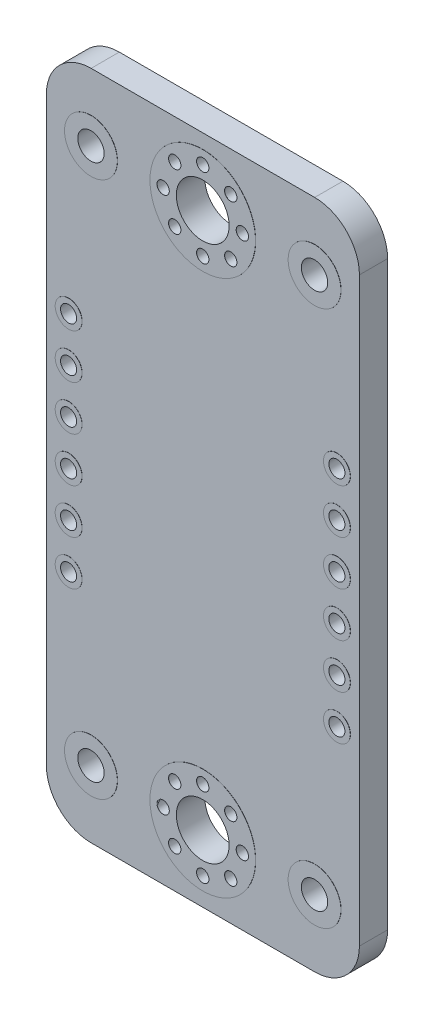
SolidWorks part; units mm, degrees
ref_plane "Front Plane" through (0, 0, 0) normal (0, 0, 1) x (1, 0, 0)
ref_plane "Top Plane" through (0, 0, 0) normal (0, 1, 0) x (1, 0, 0)
ref_plane "Right Plane" through (0, 0, 0) normal (1, 0, 0) x (0, 0, -1)
sketch "Model" plane through (0, 0, 0) normal (0, 0, 1) x (1, 0, 0)
  line L0 (2.54, 0) -> (15.24, 0)
  line L1 (0, -35.56) -> (0, -2.54)
  line L2 (15.24, -38.1) -> (2.54, -38.1)
  line L3 (17.78, -2.54) -> (17.78, -35.56)
  arc A0 (17.78, -2.54) -> (15.24, 0) centre (15.24, -2.54) ccw
  arc A1 (15.24, -38.1) -> (17.78, -35.56) centre (15.24, -35.56) ccw
  arc A2 (0, -35.56) -> (2.54, -38.1) centre (2.54, -35.56) ccw
  arc A3 (2.54, 0) -> (0, -2.54) centre (2.54, -2.54) ccw
  circle A4 centre (16.51, -15.24) radius 0.4572
  circle A5 centre (16.51, -15.24) radius 0.762 construction
  circle A6 centre (16.51, -17.78) radius 0.4572
  circle A7 centre (16.51, -17.78) radius 0.762 construction
  circle A8 centre (16.51, -20.32) radius 0.4572
  circle A9 centre (16.51, -20.32) radius 0.762 construction
  circle A10 centre (16.51, -22.86) radius 0.4572
  circle A11 centre (16.51, -22.86) radius 0.762 construction
  circle A12 centre (16.51, -25.4) radius 0.4572
  circle A13 centre (16.51, -25.4) radius 0.762 construction
  circle A14 centre (1.27, -25.4) radius 0.4572
  circle A15 centre (1.27, -25.4) radius 0.762 construction
  circle A16 centre (1.27, -22.86) radius 0.4572
  circle A17 centre (1.27, -22.86) radius 0.762 construction
  circle A18 centre (1.27, -20.32) radius 0.4572
  circle A19 centre (1.27, -20.32) radius 0.762 construction
  circle A20 centre (1.27, -17.78) radius 0.4572
  circle A21 centre (1.27, -17.78) radius 0.762 construction
  circle A22 centre (1.27, -15.24) radius 0.4572
  circle A23 centre (1.27, -15.24) radius 0.762 construction
  circle A24 centre (1.27, -12.7) radius 0.4572
  circle A25 centre (1.27, -12.7) radius 0.762 construction
  circle A26 centre (8.89, -3.81) radius 1.5
  circle A27 centre (8.89, -3.81) radius 3 construction
  circle A28 centre (11.14, -3.81) radius 0.35
  circle A29 centre (11.1399, -3.81) radius 0.75 construction
  circle A30 centre (6.64, -3.81) radius 0.35
  circle A31 centre (6.6401, -3.81) radius 0.75 construction
  circle A32 centre (8.89, -1.5601) radius 0.35
  circle A33 centre (8.89, -1.5601) radius 0.75 construction
  circle A34 centre (8.89, -6.0599) radius 0.35
  circle A35 centre (8.89, -6.0599) radius 0.75 construction
  circle A36 centre (10.4811, -5.4011) radius 0.35
  circle A37 centre (10.4811, -5.4011) radius 0.75 construction
  circle A38 centre (10.4811, -2.2189) radius 0.35
  circle A39 centre (10.4811, -2.2189) radius 0.75 construction
  circle A40 centre (7.2989, -2.2189) radius 0.35
  circle A41 centre (7.2989, -2.2189) radius 0.75 construction
  circle A42 centre (7.2989, -5.4011) radius 0.35
  circle A43 centre (7.2989, -5.4011) radius 0.75 construction
  circle A44 centre (8.89, -34.29) radius 1.5
  circle A45 centre (8.89, -34.29) radius 3 construction
  circle A46 centre (11.14, -34.29) radius 0.35
  circle A47 centre (11.1399, -34.29) radius 0.75 construction
  circle A48 centre (6.64, -34.29) radius 0.35
  circle A49 centre (6.6401, -34.29) radius 0.75 construction
  circle A50 centre (8.89, -32.0401) radius 0.35
  circle A51 centre (8.89, -32.0401) radius 0.75 construction
  circle A52 centre (8.89, -36.5399) radius 0.35
  circle A53 centre (8.89, -36.5399) radius 0.75 construction
  circle A54 centre (10.4811, -35.8811) radius 0.35
  circle A55 centre (10.4811, -35.8811) radius 0.75 construction
  circle A56 centre (10.4811, -32.6989) radius 0.35
  circle A57 centre (10.4811, -32.6989) radius 0.75 construction
  circle A58 centre (7.2989, -32.6989) radius 0.35
  circle A59 centre (7.2989, -32.6989) radius 0.75 construction
  circle A60 centre (7.2989, -35.8811) radius 0.35
  circle A61 centre (7.2989, -35.8811) radius 0.75 construction
  circle A62 centre (2.54, -3.81) radius 0.75
  circle A63 centre (2.54, -3.81) radius 1.5 construction
  circle A64 centre (15.24, -3.81) radius 0.75
  circle A65 centre (15.24, -3.81) radius 1.5 construction
  circle A66 centre (15.24, -34.29) radius 0.75
  circle A67 centre (15.24, -34.29) radius 1.5 construction
  circle A68 centre (2.54, -34.29) radius 0.75
  circle A69 centre (2.54, -34.29) radius 1.5 construction
  circle A70 centre (16.51, -12.7) radius 0.4572
  circle A71 centre (11.938, -12.446) radius 0.31 construction
  circle A72 centre (11.938, -12.446) radius 0.155 construction
  circle A73 centre (5.842, -12.446) radius 0.31 construction
  circle A74 centre (5.842, -12.446) radius 0.155 construction
  circle A75 centre (5.842, -18.796) radius 0.31 construction
  circle A76 centre (5.842, -18.796) radius 0.155 construction
  circle A77 centre (11.938, -18.796) radius 0.31 construction
  circle A78 centre (11.938, -18.796) radius 0.155 construction
  circle A79 centre (5.842, -25.146) radius 0.31 construction
  circle A80 centre (5.842, -25.146) radius 0.155 construction
  circle A81 centre (11.938, -25.146) radius 0.31 construction
  circle A82 centre (11.938, -25.146) radius 0.155 construction
  circle A83 centre (1.27, -30.48) radius 0.31 construction
  circle A84 centre (1.27, -30.48) radius 0.155 construction
  circle A85 centre (16.51, -30.48) radius 0.31 construction
  circle A86 centre (16.51, -30.48) radius 0.155 construction
  circle A87 centre (12.7, -36.83) radius 0.31 construction
  circle A88 centre (12.7, -36.83) radius 0.155 construction
  circle A89 centre (5.08, -36.83) radius 0.31 construction
  circle A90 centre (5.08, -36.83) radius 0.155 construction
  circle A91 centre (2.54, -36.83) radius 0.31 construction
  circle A92 centre (2.54, -36.83) radius 0.155 construction
  circle A93 centre (15.24, -36.83) radius 0.31 construction
  circle A94 centre (15.24, -36.83) radius 0.155 construction
  circle A95 centre (16.51, -27.94) radius 0.31 construction
  circle A96 centre (16.51, -27.94) radius 0.155 construction
  circle A97 centre (1.27, -27.94) radius 0.31 construction
  circle A98 centre (1.27, -27.94) radius 0.155 construction
  circle A99 centre (1.27, -10.16) radius 0.31 construction
  circle A100 centre (1.27, -10.16) radius 0.155 construction
  circle A101 centre (1.27, -7.62) radius 0.31 construction
  circle A102 centre (1.27, -7.62) radius 0.155 construction
  circle A103 centre (16.51, -7.62) radius 0.31 construction
  circle A104 centre (16.51, -7.62) radius 0.155 construction
  circle A105 centre (16.51, -10.16) radius 0.31 construction
  circle A106 centre (16.51, -10.16) radius 0.155 construction
  circle A107 centre (12.7, -1.27) radius 0.31 construction
  circle A108 centre (12.7, -1.27) radius 0.155 construction
  circle A109 centre (5.08, -1.27) radius 0.31 construction
  circle A110 centre (5.08, -1.27) radius 0.155 construction
  circle A111 centre (12.7, -6.35) radius 0.31 construction
  circle A112 centre (12.7, -6.35) radius 0.155 construction
  circle A113 centre (15.24, -6.35) radius 0.31 construction
  circle A114 centre (15.24, -6.35) radius 0.155 construction
  circle A115 centre (15.24, -1.27) radius 0.31 construction
  circle A116 centre (15.24, -1.27) radius 0.155 construction
  circle A117 centre (2.54, -1.27) radius 0.31 construction
  circle A118 centre (2.54, -1.27) radius 0.155 construction
  circle A119 centre (14.4694, -13.462) radius 0.31 construction
  circle A120 centre (14.4694, -13.462) radius 0.155 construction
  circle A121 centre (12.7, -15.494) radius 0.31 construction
  circle A122 centre (12.7, -15.494) radius 0.155 construction
  circle A123 centre (12.7, -21.844) radius 0.31 construction
  circle A124 centre (12.7, -21.844) radius 0.155 construction
  circle A125 centre (12.7, -28.194) radius 0.31 construction
  circle A126 centre (12.7, -28.194) radius 0.155 construction
  circle A127 centre (5.08, -28.194) radius 0.31 construction
  circle A128 centre (5.08, -28.194) radius 0.155 construction
  circle A129 centre (5.08, -21.844) radius 0.31 construction
  circle A130 centre (5.08, -21.844) radius 0.155 construction
  circle A131 centre (5.08, -15.494) radius 0.31 construction
  circle A132 centre (5.08, -15.494) radius 0.155 construction
  circle A133 centre (5.08, -9.144) radius 0.31 construction
  circle A134 centre (5.08, -9.144) radius 0.155 construction
  circle A135 centre (12.7, -9.144) radius 0.31 construction
  circle A136 centre (12.7, -9.144) radius 0.155 construction
extrude "Boss-Extrude1" add sketch "Model" along normal blind 1.6
ref_plane "Plane1" through (8.89, 0, 0) normal (1, 0, 0) x (0, 0, -1)
ref_plane "Plane2" through (0, -19.05, 0) normal (0, 1, 0) x (1, 0, 0)
sketch "Sketch1" plane through (0, 0, 1.6) normal (0, 0, 1) x (1, 0, 0)
  line L0 (17.78, -19.05) -> (0, -19.05) construction
  line L1 (17.78, -2.54) -> (17.78, -35.56) construction
  line L2 (0, -35.56) -> (0, -2.54) construction
  line L3 (8.89, -3.81) -> (8.89, -34.29) construction
  circle A0 centre (8.89, -3.81) radius 3
  circle A2 centre (2.54, -3.81) radius 1.5
  circle A6 centre (1.27, -20.32) radius 0.762
  circle A7 centre (1.27, -22.86) radius 0.762
  circle A8 centre (1.27, -25.4) radius 0.762
  circle A17 centre (2.54, -3.81) radius 0.75
  circle A18 centre (2.54, -3.81) radius 0.75 construction
  circle A19 centre (2.54, -3.81) radius 1.5 construction
  circle A20 centre (8.89, -3.81) radius 3 construction
  circle A21 centre (8.89, -3.81) radius 1.5
  circle A22 centre (8.89, -3.81) radius 1.5 construction
  circle A26 centre (8.89, -1.5601) radius 0.35
  circle A28 centre (8.89, -1.5601) radius 0.35 construction
  circle A29 centre (10.4809, -2.2192) radius 0.35
  circle A30 centre (11.1398, -3.8103) radius 0.35
  circle A31 centre (10.4807, -5.4012) radius 0.35
  circle A32 centre (8.8896, -6.0601) radius 0.35
  circle A33 centre (7.2987, -5.4009) radius 0.35
  circle A34 centre (6.6398, -3.8099) radius 0.35
  circle A35 centre (7.2989, -2.2189) radius 0.35
  circle A36 centre (15.24, -3.81) radius 1.5
  circle A37 centre (15.24, -3.81) radius 0.75
  circle A38 centre (15.24, -3.81) radius 0.75 construction
  circle A39 centre (15.24, -3.81) radius 1.5 construction
  circle A40 centre (15.24, -34.29) radius 0.75
  circle A41 centre (15.24, -34.29) radius 1.5
  circle A42 centre (7.2989, -35.8811) radius 0.35
  circle A43 centre (6.6398, -34.2901) radius 0.35
  circle A44 centre (7.2987, -32.6991) radius 0.35
  circle A45 centre (8.8896, -32.0399) radius 0.35
  circle A46 centre (10.4807, -32.6988) radius 0.35
  circle A47 centre (11.1398, -34.2897) radius 0.35
  circle A48 centre (10.4809, -35.8808) radius 0.35
  circle A49 centre (8.89, -36.5399) radius 0.35
  circle A50 centre (8.89, -34.29) radius 1.5
  circle A51 centre (2.54, -34.29) radius 0.75
  circle A52 centre (2.54, -34.29) radius 1.5
  circle A53 centre (8.89, -34.29) radius 3
  circle A54 centre (1.27, -25.4) radius 0.762 construction
  circle A57 centre (1.27, -22.86) radius 0.762 construction
  circle A58 centre (1.27, -20.32) radius 0.762 construction
  circle A59 centre (1.27, -20.32) radius 0.4572
  circle A60 centre (1.27, -22.86) radius 0.4572
  circle A61 centre (1.27, -25.4) radius 0.4572
  circle A62 centre (1.27, -20.32) radius 0.4572 construction
  circle A63 centre (1.27, -12.7) radius 0.4572
  circle A64 centre (1.27, -15.24) radius 0.4572
  circle A65 centre (1.27, -17.78) radius 0.4572
  circle A66 centre (1.27, -12.7) radius 0.762
  circle A67 centre (1.27, -15.24) radius 0.762
  circle A68 centre (1.27, -17.78) radius 0.762
  circle A69 centre (16.51, -17.78) radius 0.762
  circle A70 centre (16.51, -15.24) radius 0.762
  circle A71 centre (16.51, -12.7) radius 0.762
  circle A72 centre (16.51, -17.78) radius 0.4572
  circle A73 centre (16.51, -15.24) radius 0.4572
  circle A74 centre (16.51, -12.7) radius 0.4572
  circle A75 centre (16.51, -25.4) radius 0.4572
  circle A76 centre (16.51, -22.86) radius 0.4572
  circle A77 centre (16.51, -20.32) radius 0.4572
  circle A78 centre (16.51, -25.4) radius 0.762
  circle A79 centre (16.51, -22.86) radius 0.762
  circle A80 centre (16.51, -20.32) radius 0.762
  point P69 (8.8898, -3.8101)
  point P100 (8.8898, -34.2899)
  dimension "D1" = 8
extrude "Boss-Extrude2" add sketch "Sketch1" along normal blind 0.01
ref_plane "Plane3" through (0, 0, 0.8) normal (0, 0, 1) x (1, 0, 0)
mirror "Mirror1" about plane through (0, 0, 0.8) normal (0, 0, 1) of "Boss-Extrude2"
sketch "Sketch2" plane through (0, 0, 0) normal (0, 0, -1) x (-1, 0, 0)
  line L0 (-4.14, -8.05) -> (-2.89, -8.05)
  line L1 (-14.89, -8.05) -> (-13.64, -8.05)
  line L2 (-14.89, -8.05) -> (-14.89, -10.05)
  line L3 (-14.89, -10.05) -> (-13.64, -10.05)
  line L4 (-13.64, -8.05) -> (-13.64, -10.05)
  line L5 (-4.14, -8.05) -> (-4.14, -10.05)
  line L6 (-4.14, -10.05) -> (-2.89, -10.05)
  line L7 (-2.89, -8.05) -> (-2.89, -10.05)
  line L8 (-4.14, -14.7167) -> (-2.89, -14.7167)
  line L9 (-4.14, -14.7167) -> (-4.14, -16.7167)
  line L10 (-4.14, -16.7167) -> (-2.89, -16.7167)
  line L11 (-2.89, -14.7167) -> (-2.89, -16.7167)
  line L12 (-4.14, -21.3833) -> (-2.89, -21.3833)
  line L13 (-4.14, -21.3833) -> (-4.14, -23.3833)
  line L14 (-4.14, -23.3833) -> (-2.89, -23.3833)
  line L15 (-2.89, -21.3833) -> (-2.89, -23.3833)
  line L16 (-4.14, -28.05) -> (-2.89, -28.05)
  line L17 (-4.14, -28.05) -> (-4.14, -30.05)
  line L18 (-4.14, -30.05) -> (-2.89, -30.05)
  line L19 (-2.89, -28.05) -> (-2.89, -30.05)
  line L20 (-14.89, -14.7167) -> (-13.64, -14.7167)
  line L21 (-14.89, -14.7167) -> (-14.89, -16.7167)
  line L22 (-14.89, -16.7167) -> (-13.64, -16.7167)
  line L23 (-13.64, -14.7167) -> (-13.64, -16.7167)
  line L24 (-14.89, -21.3833) -> (-13.64, -21.3833)
  line L25 (-14.89, -21.3833) -> (-14.89, -23.3833)
  line L26 (-14.89, -23.3833) -> (-13.64, -23.3833)
  line L27 (-13.64, -21.3833) -> (-13.64, -23.3833)
  line L28 (-14.89, -28.05) -> (-13.64, -28.05)
  line L29 (-14.89, -28.05) -> (-14.89, -30.05)
  line L30 (-14.89, -30.05) -> (-13.64, -30.05)
  line L31 (-13.64, -28.05) -> (-13.64, -30.05)
  line L32 (0.88, -19.05) -> (-0.88, -19.05) construction
  line L33 (-8.89, 0.88) -> (-8.89, -0.88) construction
  point P5 (-12.7477, -27.0829)
  point P6 (-12.977, -7.4394)
  dimension "D1" = 2
  dimension "D2" = 1.25
  dimension "D5" = 11
  dimension "D6" = 22
  dimension "D7" = 12
  dimension "D8" = 6
  dimension "D3" = 2
  dimension "D4" = 4
extrude "Boss-Extrude3" add sketch "Sketch2" along normal blind 0.3
sketch "Sketch3" plane through (0, 0, 0) normal (1, 0, 0) x (0, 0, -1)
  line L0 (0.3, -8.35) -> (0.8, -8.45)
  line L1 (0.3, -8.05) -> (0.3, -10.05) construction
  line L2 (0.8, -8.45) -> (0.8, -9.65)
  line L3 (0.8, -9.65) -> (0.3, -9.75)
  line L4 (0.3, -9.75) -> (0.3, -8.35)
  line L5 (0, -9.05) -> (0.3, -9.05) construction
  line L6 (0, -8.05) -> (0, -10.05) construction
  line L7 (0.3, -9.05) -> (0.8, -9.05) construction
  dimension "D1" = 1.4
  dimension "D2" = 1.2
  dimension "D3" = 0.5
extrude "Boss-Extrude4" add sketch "Sketch3" along normal up to surface (1.25 mm away) from surface at 2.89 separate body up to face at (4.14, -9.05, -0.15) starting at face at (2.89, -9.05, -0.15)
pattern_linear "LPattern1" count 2 spacing 10.75 along (1, 0, 0) count 4 spacing 6.66 along (0, -1, 0) of "Boss-Extrude4"
